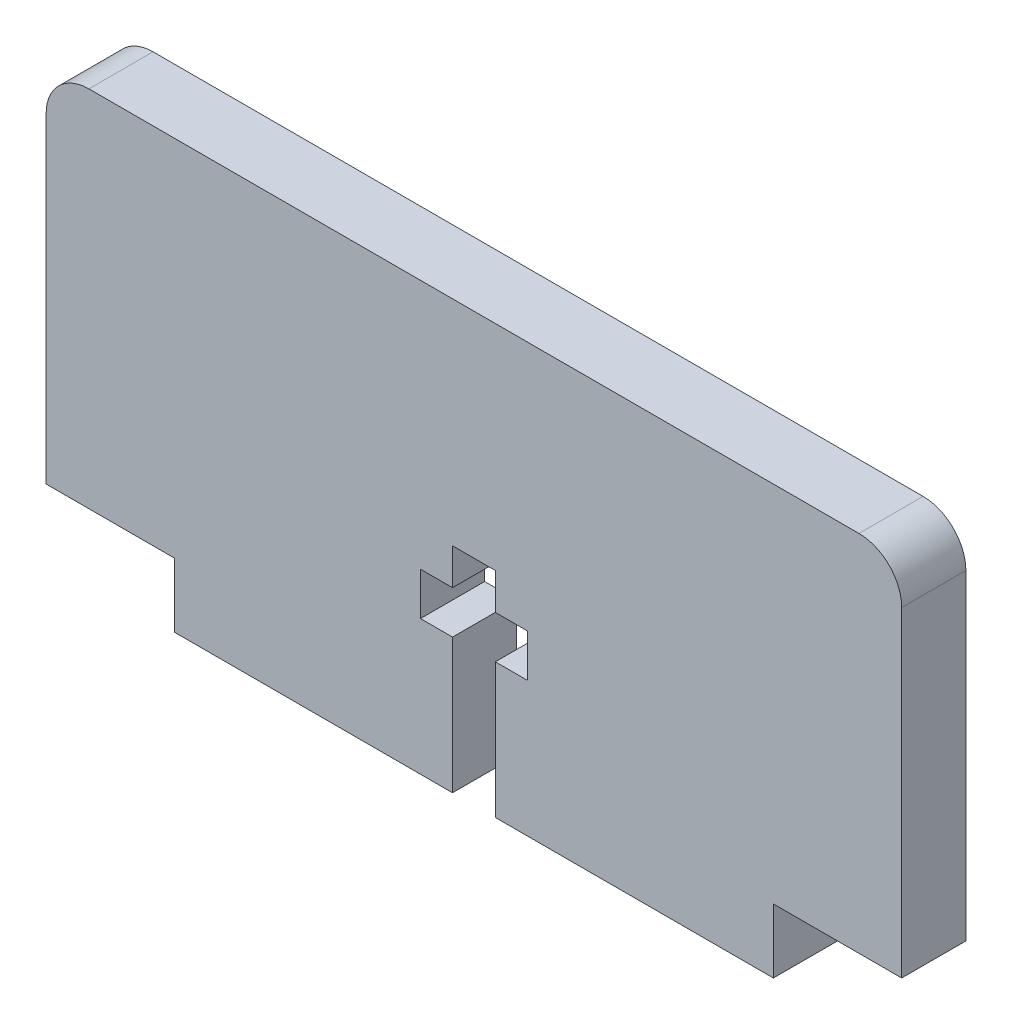
SolidWorks part; units mm, degrees
ref_plane "Plan de face" through (0, 0, 0) normal (0, 0, 1) x (1, 0, 0)
ref_plane "Plan de dessus" through (0, 0, 0) normal (0, 1, 0) x (1, 0, 0)
ref_plane "Plan de droite" through (0, 0, 0) normal (1, 0, 0) x (0, 0, -1)
sketch "Esquisse2" plane through (0, 0, 0) normal (0, 0, 1) x (1, 0, 0)
  line L0 (-100, 0) -> (100, 0)
  line L1 (100, 0) -> (100, 15)
  line L2 (100, 15) -> (100, 55.4145)
  line L3 (100, 55.4145) -> (100, 75.4145)
  line L7 (100, 75.4145) -> (100, 90)
  line L8 (90, 100) -> (-90, 100)
  line L9 (0, 0) -> (0, 100) construction
  line L10 (-100, 75.4145) -> (-100, 90)
  line L14 (-100, 55.4145) -> (-100, 75.4145)
  line L15 (-100, 15) -> (-100, 55.4145)
  line L16 (-100, 0) -> (-100, 15)
  arc A0 (100, 90) -> (90, 100) centre (90, 90) ccw
  arc A1 (-100, 90) -> (-90, 100) centre (-90, 90) cw
  dimension "D9" = 10
  dimension "D1" = 100
  dimension "D2" = 100
  dimension "D4" = 15
  dimension "D5" = 90
extrude "Boss.-Extru.1" add sketch "Esquisse2" along normal blind 15
sketch "Esquisse3" plane through (0, 0, 15) normal (0, 0, 1) x (1, 0, 0)
  line L0 (-100, 0) -> (100, 0) construction
  line L1 (-70, 15) -> (70, 15)
  line L2 (-70, 15) -> (-70, 0)
  line L3 (-70, 0) -> (70, 0)
  line L4 (70, 15) -> (70, 0)
  line L5 (-70, 15) -> (70, 0) construction
  line L6 (-70, 0) -> (70, 15) construction
  line L7 (100, 0) -> (100, 90) construction
  line L8 (-100, 90) -> (-100, 0) construction
  line L9 (0, 45.1548) -> (0, 0) construction
  line L10 (-5, 50) -> (5, 50)
  line L11 (-5, 50) -> (-5, 0)
  line L12 (-5, 0) -> (5, 0)
  line L13 (5, 50) -> (5, 0)
  line L14 (-5, 50) -> (5, 0) construction
  line L15 (-5, 0) -> (5, 50) construction
  line L16 (0, 100) -> (0, 45.1548) construction
  line L17 (-12.5, 41.5158) -> (12.5, 41.5158)
  line L18 (-12.5, 41.5158) -> (-12.5, 31.5158)
  line L19 (-12.5, 31.5158) -> (12.5, 31.5158)
  line L20 (12.5, 41.5158) -> (12.5, 31.5158)
  line L21 (-12.5, 41.5158) -> (12.5, 31.5158) construction
  line L22 (-12.5, 31.5158) -> (12.5, 41.5158) construction
  line L23 (70, 15) -> (100, 15)
  line L24 (90, 100) -> (-90, 100) construction
  line L25 (100, 0) -> (100, 90) construction
  line L26 (100, 15) -> (100, 0)
  line L27 (100, 0) -> (70, 0)
  line L28 (-70, 15) -> (-100, 15)
  line L29 (-100, 90) -> (-100, 0) construction
  line L30 (-100, 15) -> (-100, 0)
  line L31 (-100, 0) -> (-70, 0)
  point P0 (0, 7.5)
  point P11 (0, 25)
  point P20 (0, 36.5158)
  line M12 (100, 0) -> (100, 90)
  line M26 (-100, 90) -> (-100, 0)
  line M27 (-100, 0) -> (100, 0)
  dimension "D1" = 30
  dimension "D2" = 30
  dimension "D3" = 15
  dimension "D4" = 10
  dimension "D5" = 10
  dimension "D6" = 25
  dimension "D8" = 16.5158
extrude "Enlèv. mat.-Extru.1" cut sketch "Esquisse3" against normal blind 15 contours L2 L28 M26 M27 | L23 L4 M27 M12
